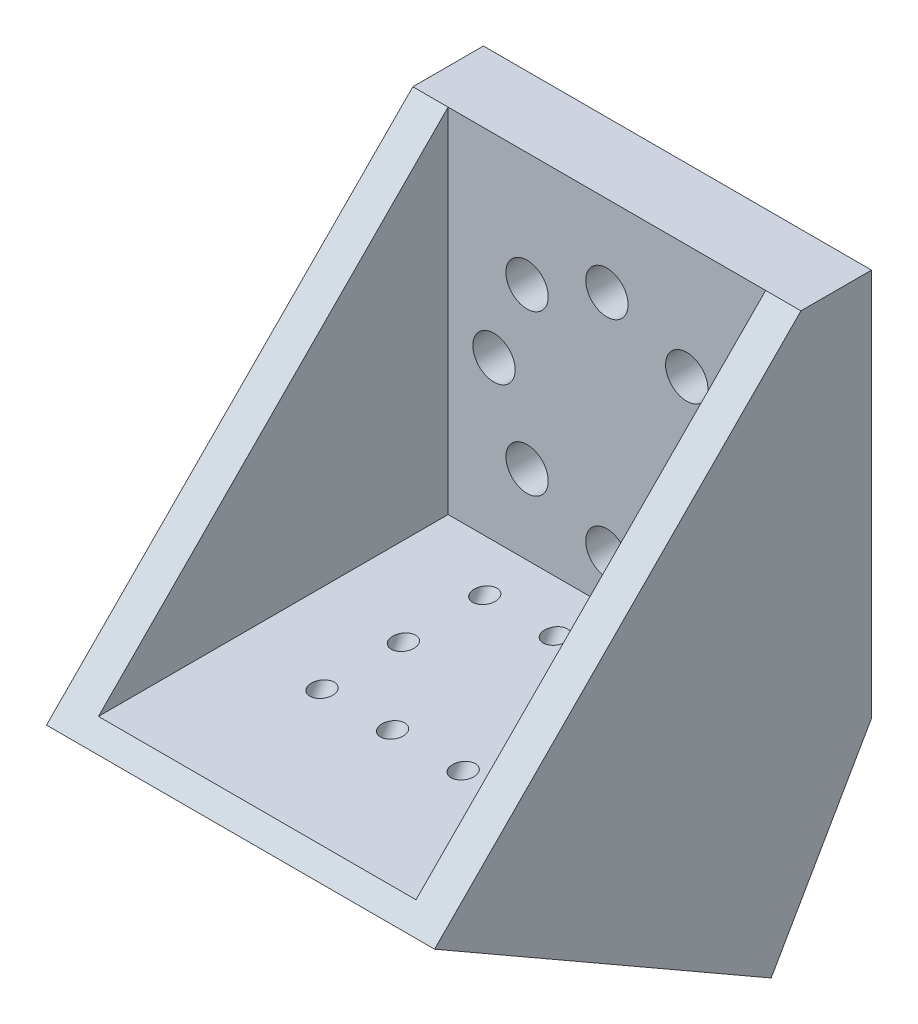
SolidWorks part; units mm, degrees
ref_plane "前视基准面" through (0, 0, 0) normal (0, 0, 1) x (1, 0, 0)
ref_plane "上视基准面" through (0, 0, 0) normal (0, 1, 0) x (1, 0, 0)
ref_plane "右视基准面" through (0, 0, 0) normal (1, 0, 0) x (0, 0, -1)
sketch "草图1" plane through (0, 0, 0) normal (0, 0, 1) x (1, 0, 0)
  line L1 (27.5, -27.5) -> (-27.5, -27.5)
  line L2 (27.5, -27.5) -> (27.5, 27.5)
  line L3 (27.5, 27.5) -> (-27.5, 27.5)
  line L4 (-27.5, -27.5) -> (-27.5, 27.5)
  line L5 (27.5, -27.5) -> (-27.5, 27.5) construction
  line L6 (27.5, 27.5) -> (-27.5, -27.5) construction
  point P0 (0, 0)
  dimension "D1" = 55
  dimension "D2" = 55
extrude "凸台-拉伸1" add sketch "草图1" along normal blind 10
sketch "草图2" plane through (27.5, 0, 0) normal (1, 0, 0) x (0, 0, -1)
  line L0 (0, -27.5) -> (-14.2199, -52.2691)
  line L1 (-14.2199, -52.2691) -> (-61.9183, -24.8856)
  line L2 (-61.9183, -24.8856) -> (-10, 27.5)
  line L4 (-10, 0) -> (-47.2687, 0) construction
  line L6 (-10, -27.5) -> (0, -27.5) construction
  line L7 (-10, 27.5) -> (0, -27.5)
  point P3 (-14.8554, -51.8994)
  dimension "D1" = 29.86
  dimension "D2" = 55
extrude "凸台-拉伸2" add sketch "草图2" against normal blind 55
ref_plane "基准面1" through (0, 0, 10) normal (0, 0, -1) x (-1, 0, 0)
sketch "草图3" plane through (0, 0, 10) normal (0, 0, -1) x (-1, 0, 0)
  line L1 (22.5, 22.5) -> (-22.5, 22.5) construction
  line L2 (22.5, 22.5) -> (22.5, -22.5)
  line L3 (22.5, -22.5) -> (-22.5, -22.5)
  line L4 (-22.5, 22.5) -> (-22.5, -22.5)
  line L5 (22.5, 22.5) -> (-22.5, -22.5) construction
  line L6 (22.5, -22.5) -> (-22.5, 22.5) construction
  line L7 (22.5, 22.5) -> (-22.5, 22.5) construction
  line L8 (22.5, 22.5) -> (22.5, 36.6251)
  line L9 (22.5, 36.6251) -> (-22.5, 36.6251)
  line L10 (-22.5, 22.5) -> (-22.5, 36.6251)
  point P0 (0, 0)
  dimension "D1" = 45
  dimension "D2" = 45
extrude "切除-拉伸1" cut sketch "草图3" against normal blind 50
sketch "草图4" plane through (0, 0, 0) normal (0, 0, -1) x (-1, 0, 0)
  line L0 (0, 0) -> (16, 0) construction
  line L1 (0, 0) -> (11.3137, -11.3137) construction
  circle A0 centre (16, 0) radius 3
  circle A1 centre (11.3137, -11.3137) radius 3
  circle A2 centre (0, -16) radius 3
  circle A3 centre (-11.3137, -11.3137) radius 3
  circle A4 centre (-16, 0) radius 3
  circle A5 centre (-11.3137, 11.3137) radius 3
  circle A6 centre (0, 16) radius 3
  circle A7 centre (11.3137, 11.3137) radius 3
  dimension "D1" = 6
  dimension "D2" = 16
  dimension "D3" = 45
extrude "切除-拉伸2" cut sketch "草图4" against normal blind 10
sketch "草图5" plane through (0, -45.4523, 26.094) normal (0, -0.8672, 0.4979) x (1, 0, 0)
  line L0 (27.5, 13.8082) -> (-27.5, 13.8082) construction
  line L1 (27.5, 41.3082) -> (27.5, -13.6918) construction
  line L2 (-27.5, 41.3082) -> (-27.5, -13.6918) construction
  line L3 (0, 41.3082) -> (0, -13.6918) construction
  line L4 (-27.5, 41.3082) -> (27.5, 41.3082) construction
  line L5 (-27.5, -13.6918) -> (27.5, -13.6918) construction
  circle A0 centre (10, 23.8082) radius 1.5
  circle A1 centre (10, 13.8082) radius 1.5
  circle A2 centre (0, 23.8082) radius 1.5
  circle A3 centre (-10, 23.8082) radius 1.5
  circle A4 centre (-10, 13.8082) radius 1.5
  circle A5 centre (-10, 3.8082) radius 1.5
  circle A6 centre (0, 3.8082) radius 1.5
  circle A7 centre (10, 3.8082) radius 1.5
  dimension "D1" = 3
  dimension "D2" = 3
  dimension "D3" = 3
  dimension "D4" = 10
  dimension "D5" = 10
  dimension "D6" = 10
  dimension "D7" = 10
extrude "切除-拉伸3" cut sketch "草图5" against normal blind 30
